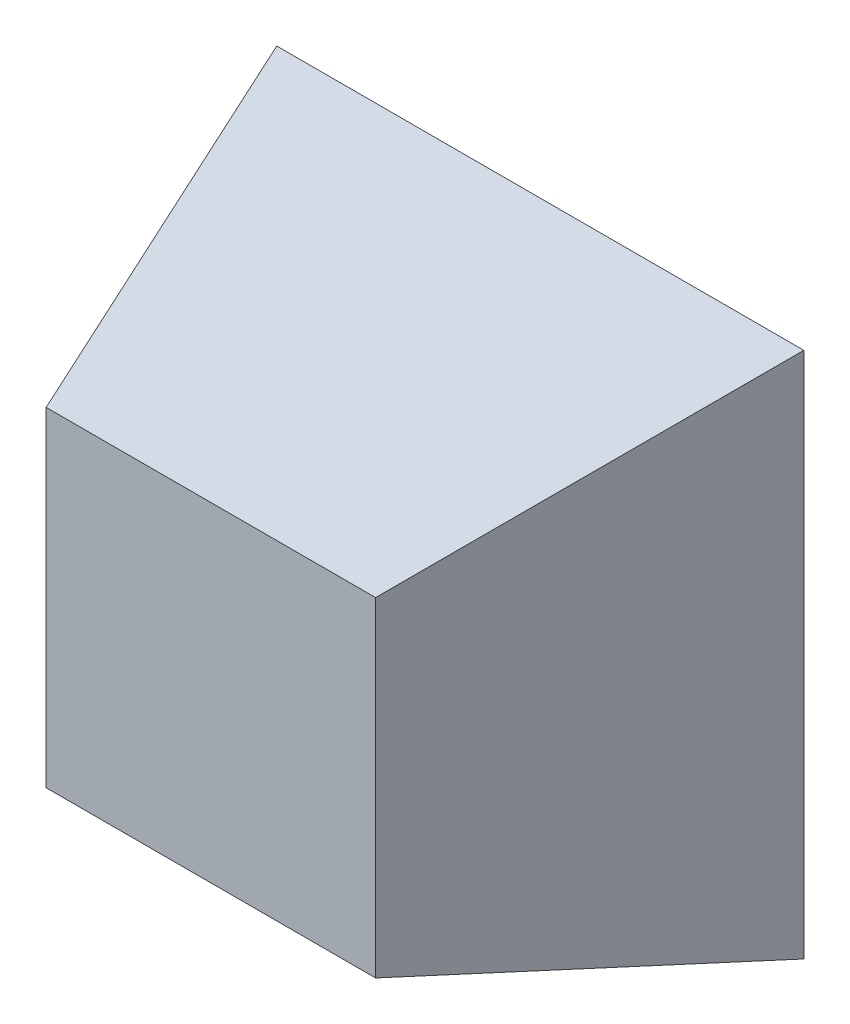
SolidWorks part; units mm, degrees
ref_plane "Plano frontal" through (0, 0, 0) normal (0, 0, 1) x (1, 0, 0)
ref_plane "Plano superior" through (0, 0, 0) normal (0, 1, 0) x (1, 0, 0)
ref_plane "Plano direito" through (0, 0, 0) normal (1, 0, 0) x (0, 0, -1)
sketch "Esboço1" plane through (0, 0, 0) normal (0, 0, 1) x (1, 0, 0)
  line L1 (-40, 40) -> (40, 40)
  line L2 (-40, 40) -> (-40, -40)
  line L3 (-40, -40) -> (40, -40)
  line L4 (40, 40) -> (40, -40)
  line L5 (-40, 40) -> (40, -40) construction
  line L6 (-40, -40) -> (40, 40) construction
  point P0 (0, 0)
  dimension "D1" = 80
  dimension "D2" = 80
extrude "Ressalto-extrusão1" add sketch "Esboço1" along normal blind 50
sketch "Esboço2" plane through (0, 0, 50) normal (0, 0, 1) x (1, 0, 0)
  line L1 (-25, 25) -> (25, 25)
  line L2 (-25, 25) -> (-25, -25)
  line L3 (-25, -25) -> (25, -25)
  line L4 (25, 25) -> (25, -25)
  line L5 (-25, 25) -> (25, -25) construction
  line L6 (-25, -25) -> (25, 25) construction
  point P0 (0, 0)
  dimension "D1" = 50
  dimension "D2" = 50
sketch "Esboço3" plane through (-40, 0, 0) normal (-1, 0, 0) x (0, 0, 1)
  line L0 (50, 25) -> (0, 40)
  line L1 (50, -25) -> (50, 25) construction
  line L2 (0, 40) -> (50, 40)
  line L3 (50, 40) -> (50, 25)
  line L4 (50, -25) -> (0, -40)
  line L5 (50, 25) -> (50, -25) construction
  line L6 (50, 25) -> (50, -25) construction
  line L7 (0, -40) -> (50, -40)
  line L8 (50, -40) -> (50, -25)
ref_plane "Plano1" through (0, -40, 0) normal (0, -1, 0) x (-1, 0, 0)
extrude "Corte-extrusão3" cut sketch "Esboço3" against normal through all
sketch "Esboço8" plane through (0, -40, 0) normal (0, -1, 0) x (-1, 0, 0)
  line L0 (25, -50) -> (40, 0)
  line L1 (25, -50) -> (-25, -50) construction
  line L2 (25, -50) -> (-25, -50) construction
  line L3 (40, 0) -> (40, -50)
  line L4 (40, -50) -> (25, -50)
  line L5 (-25, -50) -> (-40, -50)
  line L6 (25, -50) -> (-25, -50) construction
  line L7 (25, -50) -> (-25, -50) construction
  line L8 (-40, -50) -> (-40, 0)
  line L9 (-40, 0) -> (-25, -50)
extrude "Corte-extrusão4" cut sketch "Esboço8" against normal through all
